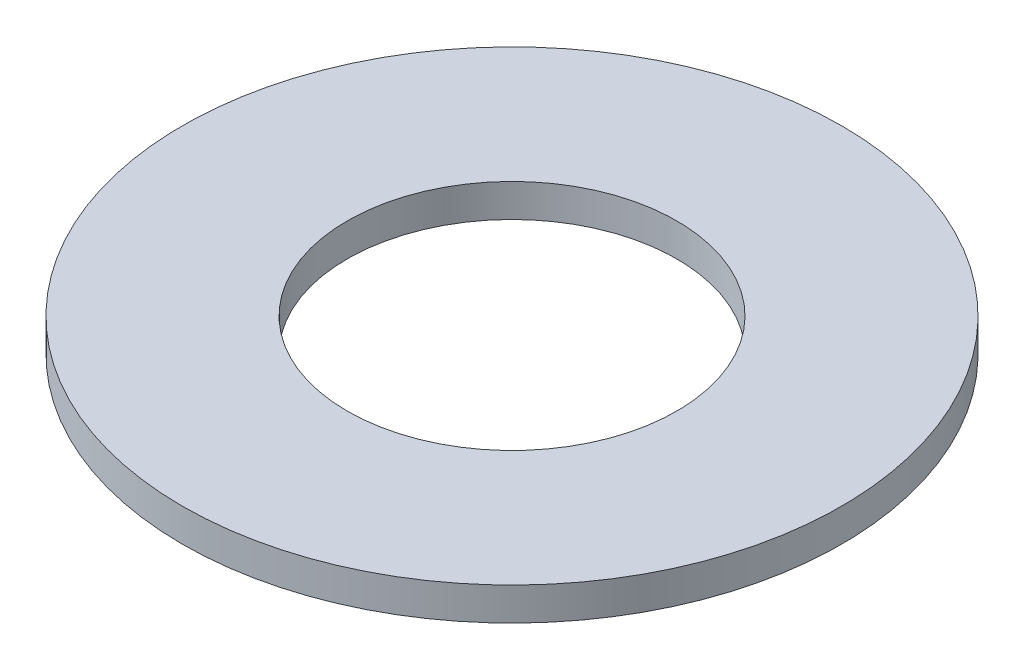
SolidWorks part; units mm, degrees
material "Alloy Steel (SS)"
ref_plane "Front Plane" through (0, 0, 0) normal (0, 0, 1) x (1, 0, 0)
ref_plane "Top Plane" through (0, 0, 0) normal (0, 1, 0) x (1, 0, 0)
ref_plane "Right Plane" through (0, 0, 0) normal (1, 0, 0) x (0, 0, -1)
sketch "Sketch1" plane through (0, 0, 0) normal (0, 1, 0) x (1, 0, 0)
  circle A0 centre (0, 0) radius 2
  circle A1 centre (0, 0) radius 1
  dimension "D1" = 4
  dimension "D2" = 2
extrude "Boss-Extrude1" add sketch "Sketch1" along normal blind 0.2
